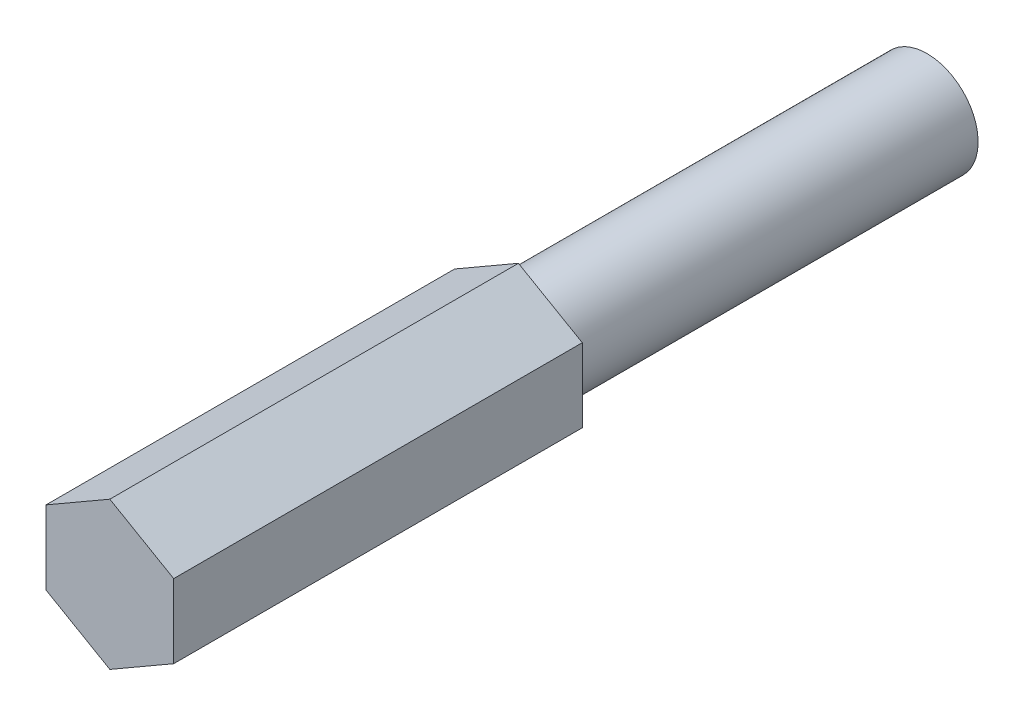
SolidWorks part; units mm, degrees
ref_plane "Front Plane" through (0, 0, 0) normal (1, 0, 0) x (0, 1, 0)
ref_plane "Top Plane" through (0, 0, 0) normal (0, 0, 1) x (0, 1, 0)
ref_plane "Right Plane" through (0, 0, 0) normal (0, 1, 0) x (-1, 0, 0)
sketch "Sketch2" plane through (0, 0, 0) normal (0, 0, 1) x (0, 1, 0)
  line L0 (-4.5827, 0) -> (4.5827, 0) construction
  line L1 (4.5827, 0) -> (2.2914, 3.9688)
  line L2 (2.2914, 3.9688) -> (-2.2914, 3.9687)
  line L3 (-2.2914, 3.9687) -> (-4.5827, 0)
  line L4 (-4.5827, 0) -> (-2.2914, -3.9688)
  line L5 (-2.2914, -3.9688) -> (2.2914, -3.9687)
  line L6 (2.2914, -3.9687) -> (4.5827, 0)
  circle A0 centre (0, 0) radius 3.9688 construction
  point P10 (0, 0)
  dimension "D1" = 7.9375
extrude "Hex" add sketch "Sketch2" along normal blind 25.4
sketch "Sketch3" plane through (0, 0, 0) normal (0, 0, -1) x (1, 0, 0)
  circle A0 centre (0, 0) radius 3.175
  dimension "D1" = 6.35
extrude "Boss-Extrude2" add sketch "Sketch3" along normal blind 25.4
